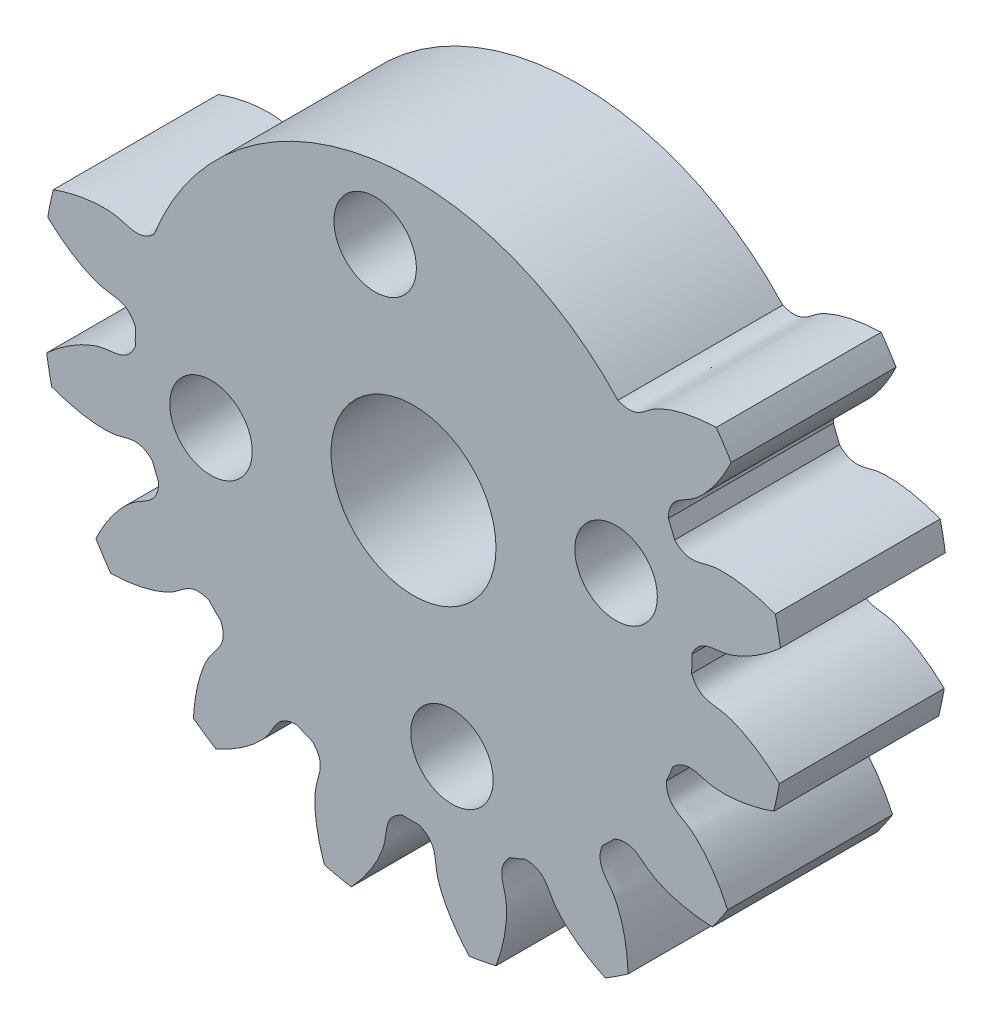
SolidWorks part; units mm, degrees
ref_plane "前视基准面" through (0, 0, 0) normal (0, 0, 1) x (1, 0, 0)
ref_plane "上视基准面" through (0, 0, 0) normal (0, 1, 0) x (1, 0, 0)
ref_plane "右视基准面" through (0, 0, 0) normal (1, 0, 0) x (0, 0, -1)
sketch "草图1" plane through (0, 0, 0) normal (0, 0, 1) x (1, 0, 0)
  circle A0 centre (-5.3365, -60.0711) radius 2
  arc A1 (0.9962, -57.7344) -> (0.8439, -57.3573) centre (-5.3365, -60.0711) ccw
  arc A2 (1.4083, -60.3357) -> (1.412, -59.929) centre (-5.3365, -60.0711) ccw
  arc A3 (0.7936, -62.8967) -> (0.9526, -62.5224) centre (-5.3365, -60.0711) ccw
  arc A4 (-0.7544, -65.0275) -> (-0.4642, -64.7425) centre (-5.3365, -60.0711) ccw
  arc A5 (-2.9999, -66.4037) -> (-2.6228, -66.2515) centre (-5.3365, -60.0711) ccw
  arc A6 (-5.6012, -66.8159) -> (-5.1945, -66.8196) centre (-5.3365, -60.0711) ccw
  arc A7 (-8.1622, -66.2012) -> (-7.7878, -66.3602) centre (-5.3365, -60.0711) ccw
  arc A8 (-10.293, -64.6532) -> (-10.008, -64.9434) centre (-5.3365, -60.0711) ccw
  arc A9 (-11.6692, -62.4077) -> (-11.517, -62.7848) centre (-5.3365, -60.0711) ccw
  arc A10 (-12.0813, -59.8064) -> (-12.085, -60.2131) centre (-5.3365, -60.0711) ccw
  arc A11 (-14.0737, -57.912) -> (-14.2089, -58.5607) centre (-5.3365, -60.0711) ccw
  arc A12 (-0.3801, -55.4889) -> (-11.6257, -57.6197) centre (-5.3365, -60.0711) ccw
  arc A13 (2.3683, -55.4197) -> (2.0051, -54.8653) centre (-5.3365, -60.0711) ccw
  arc A14 (3.5618, -58.7222) -> (3.4385, -58.0711) centre (-5.3365, -60.0711) ccw
  arc A15 (3.4007, -62.2302) -> (3.5358, -61.5814) centre (-5.3365, -60.0711) ccw
  arc A16 (1.9093, -65.4094) -> (2.2825, -64.8617) centre (-5.3365, -60.0711) ccw
  arc A17 (-0.6851, -67.7759) -> (-0.1308, -67.4127) centre (-5.3365, -60.0711) ccw
  arc A18 (-3.9877, -68.9694) -> (-3.3366, -68.846) centre (-5.3365, -60.0711) ccw
  arc A19 (-7.4956, -68.8082) -> (-6.8468, -68.9434) centre (-5.3365, -60.0711) ccw
  arc A20 (-10.6748, -67.3169) -> (-10.1272, -67.6901) centre (-5.3365, -60.0711) ccw
  arc A21 (-13.0414, -64.7225) -> (-12.6782, -65.2768) centre (-5.3365, -60.0711) ccw
  arc A22 (-14.2349, -61.4199) -> (-14.1115, -62.071) centre (-5.3365, -60.0711) ccw
  circle A23 centre (-10.2491, -61.0019) radius 1
  circle A24 centre (-4.4057, -64.9836) radius 1
  circle A25 centre (-0.4239, -59.1402) radius 1
  circle A26 centre (-6.2674, -55.1585) radius 1
  spline S0 degree 3 poles (-0.3801, -55.4889) (0.0578, -55.6734) (0.25, -55.383) (0.5366, -55.2105) (0.5782, -55.1872) (0.6371, -55.1572) (0.7082, -55.1245) (0.7916, -55.09) (0.8876, -55.0548) (0.9963, -55.0198) (1.118, -54.9858) (1.2527, -54.954) (1.4003, -54.9253) (1.5608, -54.9007) (1.7341, -54.8812) (1.8837, -54.8703) (1.9755, -54.8663) (2.0051, -54.8653) knots 0 0 0 0 0.200958 0.205848 0.217584 0.231929 0.248881 0.268441 0.29061 0.315386 0.342771 0.372764 0.405364 0.440573 0.47839 0.518814 0.53812 0.53812 0.53812 0.53812
  spline S1 degree 3 poles (0.8439, -57.3573) (0.8497, -56.8821) (1.1927, -56.8219) (1.4653, -56.6281) (1.5032, -56.5993) (1.5543, -56.5572) (1.6127, -56.5052) (1.6775, -56.4425) (1.7482, -56.3685) (1.8238, -56.2828) (1.9035, -56.1848) (1.9864, -56.0741) (2.0717, -55.9502) (2.1584, -55.8129) (2.2455, -55.6618) (2.3152, -55.5289) (2.3555, -55.4464) (2.3683, -55.4197) knots 0 0 0 0 0.200958 0.205848 0.217584 0.231929 0.248881 0.268441 0.29061 0.315386 0.342771 0.372764 0.405364 0.440573 0.47839 0.518814 0.53812 0.53812 0.53812 0.53812
  spline S2 degree 3 poles (0.9962, -57.7344) (1.3301, -58.0725) (1.6188, -57.8778) (1.9496, -57.828) (1.9969, -57.8224) (2.0629, -57.8172) (2.141, -57.8142) (2.2312, -57.8143) (2.3334, -57.8185) (2.4473, -57.8277) (2.5727, -57.843) (2.7093, -57.8651) (2.8567, -57.8951) (3.0144, -57.9338) (3.182, -57.982) (3.3244, -58.0293) (3.4107, -58.0607) (3.4385, -58.0711) knots 0 0 0 0 0.200958 0.205848 0.217584 0.231929 0.248881 0.268441 0.29061 0.315386 0.342771 0.372764 0.405364 0.440573 0.47839 0.518814 0.53812 0.53812 0.53812 0.53812
  spline S3 degree 3 poles (1.412, -59.929) (1.5991, -59.4922) (1.939, -59.5678) (2.2651, -59.4931) (2.3112, -59.481) (2.3745, -59.4617) (2.4483, -59.436) (2.5322, -59.4029) (2.6258, -59.3616) (2.7284, -59.3113) (2.8396, -59.2513) (2.9586, -59.1807) (3.0848, -59.0989) (3.2174, -59.0052) (3.3557, -58.8989) (3.4709, -58.8029) (3.5398, -58.7421) (3.5618, -58.7222) knots 0 0 0 0 0.200958 0.205848 0.217584 0.231929 0.248881 0.268441 0.29061 0.315386 0.342771 0.372764 0.405364 0.440573 0.47839 0.518814 0.53812 0.53812 0.53812 0.53812
  spline S4 degree 3 poles (1.4083, -60.3357) (1.5875, -60.7758) (1.9287, -60.7064) (2.2534, -60.787) (2.2992, -60.8) (2.3621, -60.8204) (2.4355, -60.8475) (2.5188, -60.8822) (2.6116, -60.9251) (2.7133, -60.9773) (2.8233, -61.0393) (2.941, -61.112) (3.0657, -61.1961) (3.1966, -61.2922) (3.333, -61.401) (3.4464, -61.4991) (3.5141, -61.5611) (3.5358, -61.5814) knots 0 0 0 0 0.200958 0.205848 0.217584 0.231929 0.248881 0.268441 0.29061 0.315386 0.342771 0.372764 0.405364 0.440573 0.47839 0.518814 0.53812 0.53812 0.53812 0.53812
  spline S5 degree 3 poles (0.9526, -62.5224) (1.2927, -62.1904) (1.5778, -62.3904) (1.9076, -62.4461) (1.9548, -62.4526) (2.0207, -62.459) (2.0988, -62.4634) (2.189, -62.465) (2.2912, -62.4626) (2.4053, -62.4555) (2.5309, -62.4425) (2.6679, -62.4229) (2.8158, -62.3956) (2.9742, -62.3598) (3.1426, -62.3145) (3.2858, -62.2699) (3.3727, -62.24) (3.4007, -62.2302) knots 0 0 0 0 0.200958 0.205848 0.217584 0.231929 0.248881 0.268441 0.29061 0.315386 0.342771 0.372764 0.405364 0.440573 0.47839 0.518814 0.53812 0.53812 0.53812 0.53812
  spline S6 degree 3 poles (0.7936, -62.8967) (0.7907, -63.3719) (1.1325, -63.4383) (1.4016, -63.6371) (1.439, -63.6665) (1.4893, -63.7095) (1.5467, -63.7626) (1.6104, -63.8265) (1.6797, -63.9017) (1.7538, -63.9888) (1.8317, -64.0882) (1.9126, -64.2005) (1.9956, -64.3258) (2.0798, -64.4647) (2.1641, -64.6174) (2.2314, -64.7515) (2.2702, -64.8347) (2.2825, -64.8617) knots 0 0 0 0 0.200958 0.205848 0.217584 0.231929 0.248881 0.268441 0.29061 0.315386 0.342771 0.372764 0.405364 0.440573 0.47839 0.518814 0.53812 0.53812 0.53812 0.53812
  spline S7 degree 3 poles (-0.4642, -64.7425) (-0.023, -64.566) (0.1639, -64.8598) (0.4473, -65.0376) (0.4884, -65.0616) (0.5468, -65.0927) (0.6173, -65.1267) (0.7, -65.1626) (0.7954, -65.1996) (0.9035, -65.2366) (1.0245, -65.2728) (1.1586, -65.307) (1.3056, -65.3384) (1.4657, -65.3659) (1.6387, -65.3886) (1.788, -65.4021) (1.8797, -65.4078) (1.9093, -65.4094) knots 0 0 0 0 0.200958 0.205848 0.217584 0.231929 0.248881 0.268441 0.29061 0.315386 0.342771 0.372764 0.405364 0.440573 0.47839 0.518814 0.53812 0.53812 0.53812 0.53812
  spline S8 degree 3 poles (-0.7544, -65.0275) (-0.9389, -65.4654) (-0.6485, -65.6576) (-0.4759, -65.9442) (-0.4527, -65.9857) (-0.4226, -66.0447) (-0.3899, -66.1157) (-0.3555, -66.1991) (-0.3203, -66.2951) (-0.2852, -66.4039) (-0.2513, -66.5256) (-0.2195, -66.6602) (-0.1908, -66.8078) (-0.1662, -66.9684) (-0.1466, -67.1417) (-0.1358, -67.2913) (-0.1318, -67.3831) (-0.1308, -67.4127) knots 0 0 0 0 0.200958 0.205848 0.217584 0.231929 0.248881 0.268441 0.29061 0.315386 0.342771 0.372764 0.405364 0.440573 0.47839 0.518814 0.53812 0.53812 0.53812 0.53812
  spline S9 degree 3 poles (-2.6228, -66.2515) (-2.1476, -66.2573) (-2.0874, -66.6002) (-1.8936, -66.8729) (-1.8648, -66.9108) (-1.8227, -66.9619) (-1.7706, -67.0202) (-1.7079, -67.0851) (-1.634, -67.1558) (-1.5483, -67.2314) (-1.4503, -67.3111) (-1.3395, -67.394) (-1.2157, -67.4793) (-1.0783, -67.566) (-0.9272, -67.6531) (-0.7944, -67.7228) (-0.7119, -67.7631) (-0.6851, -67.7759) knots 0 0 0 0 0.200958 0.205848 0.217584 0.231929 0.248881 0.268441 0.29061 0.315386 0.342771 0.372764 0.405364 0.440573 0.47839 0.518814 0.53812 0.53812 0.53812 0.53812
  spline S10 degree 3 poles (-2.9999, -66.4037) (-3.338, -66.7377) (-3.1432, -67.0264) (-3.0935, -67.3572) (-3.0879, -67.4045) (-3.0827, -67.4704) (-3.0797, -67.5486) (-3.0798, -67.6388) (-3.084, -67.741) (-3.0932, -67.8549) (-3.1084, -67.9803) (-3.1306, -68.1169) (-3.1605, -68.2642) (-3.1992, -68.422) (-3.2475, -68.5896) (-3.2948, -68.7319) (-3.3262, -68.8182) (-3.3366, -68.846) knots 0 0 0 0 0.200958 0.205848 0.217584 0.231929 0.248881 0.268441 0.29061 0.315386 0.342771 0.372764 0.405364 0.440573 0.47839 0.518814 0.53812 0.53812 0.53812 0.53812
  spline S11 degree 3 poles (-5.1945, -66.8196) (-4.7577, -67.0067) (-4.8333, -67.3466) (-4.7586, -67.6727) (-4.7465, -67.7188) (-4.7272, -67.782) (-4.7014, -67.8559) (-4.6683, -67.9398) (-4.627, -68.0334) (-4.5768, -68.136) (-4.5167, -68.2472) (-4.4462, -68.3662) (-4.3644, -68.4923) (-4.2707, -68.625) (-4.1644, -68.7633) (-4.0683, -68.8785) (-4.0075, -68.9473) (-3.9877, -68.9694) knots 0 0 0 0 0.200958 0.205848 0.217584 0.231929 0.248881 0.268441 0.29061 0.315386 0.342771 0.372764 0.405364 0.440573 0.47839 0.518814 0.53812 0.53812 0.53812 0.53812
  spline S12 degree 3 poles (-5.6012, -66.8159) (-6.0413, -66.9951) (-5.9719, -67.3363) (-6.0525, -67.6609) (-6.0654, -67.7068) (-6.0859, -67.7697) (-6.113, -67.843) (-6.1476, -67.9264) (-6.1906, -68.0192) (-6.2427, -68.1209) (-6.3048, -68.2309) (-6.3775, -68.3486) (-6.4616, -68.4733) (-6.5577, -68.6042) (-6.6664, -68.7406) (-6.7646, -68.854) (-6.8266, -68.9217) (-6.8468, -68.9434) knots 0 0 0 0 0.200958 0.205848 0.217584 0.231929 0.248881 0.268441 0.29061 0.315386 0.342771 0.372764 0.405364 0.440573 0.47839 0.518814 0.53812 0.53812 0.53812 0.53812
  spline S13 degree 3 poles (-7.7878, -66.3602) (-7.4559, -66.7003) (-7.6558, -66.9854) (-7.7116, -67.3152) (-7.7181, -67.3624) (-7.7244, -67.4283) (-7.7289, -67.5063) (-7.7304, -67.5966) (-7.7281, -67.6988) (-7.7209, -67.8128) (-7.708, -67.9385) (-7.6883, -68.0755) (-7.6611, -68.2233) (-7.6252, -68.3817) (-7.58, -68.5502) (-7.5353, -68.6934) (-7.5055, -68.7803) (-7.4956, -68.8082) knots 0 0 0 0 0.200958 0.205848 0.217584 0.231929 0.248881 0.268441 0.29061 0.315386 0.342771 0.372764 0.405364 0.440573 0.47839 0.518814 0.53812 0.53812 0.53812 0.53812
  spline S14 degree 3 poles (-8.1622, -66.2012) (-8.6374, -66.1983) (-8.7038, -66.5401) (-8.9025, -66.8092) (-8.932, -66.8466) (-8.975, -66.8969) (-9.0281, -66.9543) (-9.092, -67.018) (-9.1672, -67.0873) (-9.2543, -67.1613) (-9.3537, -67.2392) (-9.4659, -67.3202) (-9.5913, -67.4032) (-9.7302, -67.4873) (-9.8829, -67.5717) (-10.0169, -67.639) (-10.1002, -67.6778) (-10.1272, -67.6901) knots 0 0 0 0 0.200958 0.205848 0.217584 0.231929 0.248881 0.268441 0.29061 0.315386 0.342771 0.372764 0.405364 0.440573 0.47839 0.518814 0.53812 0.53812 0.53812 0.53812
  spline S15 degree 3 poles (-10.008, -64.9434) (-9.8315, -65.3846) (-10.1253, -65.5715) (-10.303, -65.8549) (-10.3271, -65.896) (-10.3582, -65.9544) (-10.3921, -66.0248) (-10.4281, -66.1076) (-10.465, -66.2029) (-10.5021, -66.3111) (-10.5382, -66.4321) (-10.5725, -66.5662) (-10.6039, -66.7132) (-10.6314, -66.8733) (-10.6541, -67.0462) (-10.6676, -67.1956) (-10.6733, -67.2873) (-10.6748, -67.3169) knots 0 0 0 0 0.200958 0.205848 0.217584 0.231929 0.248881 0.268441 0.29061 0.315386 0.342771 0.372764 0.405364 0.440573 0.47839 0.518814 0.53812 0.53812 0.53812 0.53812
  spline S16 degree 3 poles (-10.293, -64.6532) (-10.7309, -64.4687) (-10.9231, -64.7591) (-11.2097, -64.9316) (-11.2512, -64.9549) (-11.3102, -64.9849) (-11.3812, -65.0176) (-11.4646, -65.0521) (-11.5606, -65.0873) (-11.6694, -65.1224) (-11.7911, -65.1563) (-11.9257, -65.1881) (-12.0733, -65.2168) (-12.2338, -65.2414) (-12.4072, -65.261) (-12.5568, -65.2718) (-12.6485, -65.2758) (-12.6782, -65.2768) knots 0 0 0 0 0.200958 0.205848 0.217584 0.231929 0.248881 0.268441 0.29061 0.315386 0.342771 0.372764 0.405364 0.440573 0.47839 0.518814 0.53812 0.53812 0.53812 0.53812
  spline S17 degree 3 poles (-11.517, -62.7848) (-11.5227, -63.26) (-11.8657, -63.3202) (-12.1384, -63.514) (-12.1763, -63.5428) (-12.2274, -63.5849) (-12.2857, -63.6369) (-12.3506, -63.6996) (-12.4212, -63.7736) (-12.4968, -63.8593) (-12.5765, -63.9573) (-12.6595, -64.068) (-12.7447, -64.1919) (-12.8314, -64.3292) (-12.9186, -64.4804) (-12.9882, -64.6132) (-13.0286, -64.6957) (-13.0414, -64.7225) knots 0 0 0 0 0.200958 0.205848 0.217584 0.231929 0.248881 0.268441 0.29061 0.315386 0.342771 0.372764 0.405364 0.440573 0.47839 0.518814 0.53812 0.53812 0.53812 0.53812
  spline S18 degree 3 poles (-11.6692, -62.4077) (-12.0032, -62.0696) (-12.2919, -62.2643) (-12.6227, -62.3141) (-12.6699, -62.3197) (-12.7359, -62.3249) (-12.814, -62.3279) (-12.9043, -62.3278) (-13.0064, -62.3236) (-13.1204, -62.3144) (-13.2458, -62.2992) (-13.3823, -62.277) (-13.5297, -62.2471) (-13.6874, -62.2084) (-13.8551, -62.1601) (-13.9974, -62.1128) (-14.0837, -62.0814) (-14.1115, -62.071) knots 0 0 0 0 0.200958 0.205848 0.217584 0.231929 0.248881 0.268441 0.29061 0.315386 0.342771 0.372764 0.405364 0.440573 0.47839 0.518814 0.53812 0.53812 0.53812 0.53812
  spline S19 degree 3 poles (-12.085, -60.2131) (-12.2722, -60.6499) (-12.6121, -60.5743) (-12.9382, -60.649) (-12.9842, -60.6611) (-13.0475, -60.6804) (-13.1213, -60.7062) (-13.2053, -60.7393) (-13.2988, -60.7805) (-13.4015, -60.8308) (-13.5126, -60.8908) (-13.6316, -60.9614) (-13.7578, -61.0432) (-13.8905, -61.1369) (-14.0288, -61.2432) (-14.144, -61.3392) (-14.2128, -61.4) (-14.2349, -61.4199) knots 0 0 0 0 0.200958 0.205848 0.217584 0.231929 0.248881 0.268441 0.29061 0.315386 0.342771 0.372764 0.405364 0.440573 0.47839 0.518814 0.53812 0.53812 0.53812 0.53812
  spline S20 degree 3 poles (-12.0813, -59.8064) (-12.2605, -59.3663) (-12.6017, -59.4357) (-12.9264, -59.3551) (-12.9722, -59.3422) (-13.0352, -59.3217) (-13.1085, -59.2946) (-13.1918, -59.26) (-13.2846, -59.217) (-13.3863, -59.1649) (-13.4964, -59.1028) (-13.6141, -59.0301) (-13.7387, -58.946) (-13.8697, -58.8499) (-14.0061, -58.7412) (-14.1195, -58.643) (-14.1872, -58.581) (-14.2089, -58.5607) knots 0 0 0 0 0.200958 0.205848 0.217584 0.231929 0.248881 0.268441 0.29061 0.315386 0.342771 0.372764 0.405364 0.440573 0.47839 0.518814 0.53812 0.53812 0.53812 0.53812
  spline S21 degree 3 poles (-11.6257, -57.6197) (-11.9658, -57.9517) (-12.2509, -57.7517) (-12.5807, -57.696) (-12.6279, -57.6895) (-12.6937, -57.6831) (-12.7718, -57.6787) (-12.862, -57.6772) (-12.9642, -57.6795) (-13.0783, -57.6867) (-13.204, -57.6996) (-13.3409, -57.7192) (-13.4888, -57.7465) (-13.6472, -57.7823) (-13.8157, -57.8276) (-13.9589, -57.8722) (-14.0457, -57.9021) (-14.0737, -57.912) knots 0 0 0 0 0.200958 0.205848 0.217584 0.231929 0.248881 0.268441 0.29061 0.315386 0.342771 0.372764 0.405364 0.440573 0.47839 0.518814 0.53812 0.53812 0.53812 0.53812
extrude "凸台-拉伸1" add sketch "草图1" along normal blind 4
